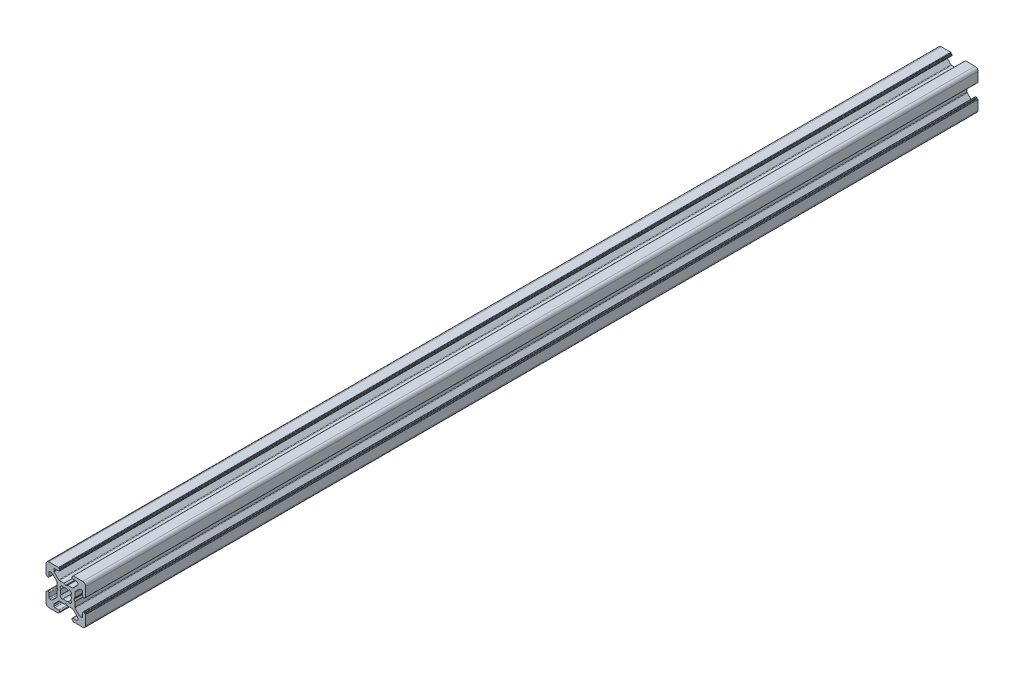
SolidWorks part; units mm, degrees
material "3.1355 (EN-AW 2024)"
ref_plane "Спереди" through (0, 0, 0) normal (0, 0, 1) x (1, 0, 0)
ref_plane "Сверху" through (0, 0, 0) normal (0, 1, 0) x (1, 0, 0)
ref_plane "Справа" through (0, 0, 0) normal (1, 0, 0) x (0, 0, -1)
sketch "Model" plane through (0, 0, 0) normal (0, 0, 1) x (1, 0, 0)
  line L0 (-1.9139, 2.9896) -> (-1.2582, 2.4453)
  line L1 (1.2582, 2.4453) -> (1.9139, 2.9896)
  line L2 (2.9922, 1.9099) -> (2.4453, 1.2582)
  line L3 (2.4453, -1.2582) -> (2.9922, -1.9099)
  line L4 (1.9139, -2.9896) -> (1.2582, -2.4453)
  line L5 (-1.2582, -2.4453) -> (-1.9139, -2.9896)
  line L6 (-2.9922, -1.9099) -> (-2.4453, -1.2582)
  line L7 (-2.4453, 1.2582) -> (-2.9922, 1.9099)
  line L8 (5.6579, 4.5972) -> (5.7096, 4.7904)
  line L9 (5.7096, 4.7904) -> (5.9028, 4.8421)
  line L10 (5.9028, 4.8421) -> (6.9142, 5.8536)
  line L11 (7.2678, 6) -> (8, 6)
  line L12 (8.5, 5.5) -> (8.5, 3.6)
  line L13 (9, 3.1) -> (9.3, 3.1)
  line L14 (9.5, 3.3) -> (9.5, 3.35)
  line L15 (9.7, 3.55) -> (9.8, 3.55)
  line L16 (10, 3.75) -> (10, 8.5)
  line L17 (8.5, 10) -> (3.75, 10)
  line L18 (3.55, 9.8) -> (3.55, 9.7)
  line L19 (3.35, 9.5) -> (3.3, 9.5)
  line L20 (3.1, 9.3) -> (3.1, 9)
  line L21 (3.6, 8.5) -> (5.5, 8.5)
  line L22 (6, 8) -> (6, 7.2678)
  line L23 (5.8536, 6.9142) -> (3.5858, 4.6464)
  line L24 (3.2322, 4.5) -> (0.9536, 4.5)
  line L25 (0.8536, 4.4732) -> (0.1, 4.0381)
  line L26 (-0.1, 4.0381) -> (-0.8536, 4.4732)
  line L27 (-0.9536, 4.5) -> (-3.2322, 4.5)
  line L28 (-3.5858, 4.6464) -> (-5.8536, 6.9142)
  line L29 (-6, 7.2678) -> (-6, 8)
  line L30 (-5.5, 8.5) -> (-3.6, 8.5)
  line L31 (-3.1, 9) -> (-3.1, 9.3)
  line L32 (-3.3, 9.5) -> (-3.35, 9.5)
  line L33 (-3.55, 9.7) -> (-3.55, 9.8)
  line L34 (-3.75, 10) -> (-8.5, 10)
  line L35 (-10, 8.5) -> (-10, 3.75)
  line L36 (-9.8, 3.55) -> (-9.7, 3.55)
  line L37 (-9.5, 3.35) -> (-9.5, 3.3)
  line L38 (-9.3, 3.1) -> (-9, 3.1)
  line L39 (-8.5, 3.6) -> (-8.5, 5.5)
  line L40 (-8, 6) -> (-7.2678, 6)
  line L41 (-6.9142, 5.8536) -> (-4.6464, 3.5858)
  line L42 (-4.5, 3.2322) -> (-4.5, 0.9536)
  line L43 (-4.4732, 0.8536) -> (-4.0381, 0.1)
  line L44 (-4.0381, -0.1) -> (-4.4732, -0.8536)
  line L45 (-4.5, -0.9536) -> (-4.5, -3.2322)
  line L46 (-4.6464, -3.5858) -> (-6.9142, -5.8536)
  line L47 (-7.2678, -6) -> (-8, -6)
  line L48 (-8.5, -5.5) -> (-8.5, -3.6)
  line L49 (-9, -3.1) -> (-9.3, -3.1)
  line L50 (-9.5, -3.3) -> (-9.5, -3.35)
  line L51 (-9.7, -3.55) -> (-9.8, -3.55)
  line L52 (-10, -3.75) -> (-10, -8.5)
  line L53 (-8.5, -10) -> (-3.75, -10)
  line L54 (-3.55, -9.8) -> (-3.55, -9.7)
  line L55 (-3.35, -9.5) -> (-3.3, -9.5)
  line L56 (-3.1, -9.3) -> (-3.1, -9)
  line L57 (-3.6, -8.5) -> (-5.5, -8.5)
  line L58 (-6, -8) -> (-6, -7.2678)
  line L59 (-5.8536, -6.9142) -> (-3.5858, -4.6464)
  line L60 (-3.2322, -4.5) -> (-0.9536, -4.5)
  line L61 (-0.8536, -4.4732) -> (-0.1, -4.0381)
  line L62 (0.1, -4.0381) -> (0.8536, -4.4732)
  line L63 (0.9536, -4.5) -> (3.2322, -4.5)
  line L64 (3.5858, -4.6464) -> (5.8536, -6.9142)
  line L65 (6, -7.2678) -> (6, -8)
  line L66 (5.5, -8.5) -> (3.6, -8.5)
  line L67 (3.1, -9) -> (3.1, -9.3)
  line L68 (3.3, -9.5) -> (3.35, -9.5)
  line L69 (3.55, -9.7) -> (3.55, -9.8)
  line L70 (3.75, -10) -> (8.5, -10)
  line L71 (10, -8.5) -> (10, -3.75)
  line L72 (9.8, -3.55) -> (9.7, -3.55)
  line L73 (9.5, -3.35) -> (9.5, -3.3)
  line L74 (9.3, -3.1) -> (9, -3.1)
  line L75 (8.5, -3.6) -> (8.5, -5.5)
  line L76 (8, -6) -> (7.2678, -6)
  line L77 (6.9142, -5.8536) -> (4.6464, -3.5858)
  line L78 (4.5, -3.2322) -> (4.5, -0.9536)
  line L79 (4.4732, -0.8536) -> (4.0381, -0.1)
  line L80 (4.0381, 0.1) -> (4.4732, 0.8536)
  line L81 (4.5, 0.9536) -> (4.5, 3.2322)
  line L82 (4.6464, 3.5858) -> (5.6579, 4.5972)
  arc A0 (-1.9139, 2.9896) -> (-2.9922, 1.9099) centre (0, 0) ccw
  arc A1 (1.2582, 2.4453) -> (-1.2582, 2.4453) centre (0, 0) ccw
  arc A2 (2.9922, 1.9099) -> (1.9139, 2.9896) centre (0, 0) ccw
  arc A3 (2.4453, -1.2582) -> (2.4453, 1.2582) centre (0, 0) ccw
  arc A4 (1.9139, -2.9896) -> (2.9922, -1.9099) centre (0, 0) ccw
  arc A5 (-1.2582, -2.4453) -> (1.2582, -2.4453) centre (0, 0) ccw
  arc A6 (-2.9922, -1.9099) -> (-1.9139, -2.9896) centre (0, 0) ccw
  arc A7 (-2.4453, 1.2582) -> (-2.4453, -1.2582) centre (0, 0) ccw
  arc A8 (7.2678, 6) -> (6.9142, 5.8536) centre (7.2678, 5.5) ccw
  arc A9 (8.5, 5.5) -> (8, 6) centre (8, 5.5) ccw
  arc A10 (8.5, 3.6) -> (9, 3.1) centre (9, 3.6) ccw
  arc A11 (9.3, 3.1) -> (9.5, 3.3) centre (9.3, 3.3) ccw
  arc A12 (9.7, 3.55) -> (9.5, 3.35) centre (9.7, 3.35) ccw
  arc A13 (9.8, 3.55) -> (10, 3.75) centre (9.8, 3.75) ccw
  arc A14 (10, 8.5) -> (8.5, 10) centre (8.5, 8.5) ccw
  arc A15 (3.75, 10) -> (3.55, 9.8) centre (3.75, 9.8) ccw
  arc A16 (3.35, 9.5) -> (3.55, 9.7) centre (3.35, 9.7) ccw
  arc A17 (3.3, 9.5) -> (3.1, 9.3) centre (3.3, 9.3) ccw
  arc A18 (3.1, 9) -> (3.6, 8.5) centre (3.6, 9) ccw
  arc A19 (6, 8) -> (5.5, 8.5) centre (5.5, 8) ccw
  arc A20 (5.8536, 6.9142) -> (6, 7.2678) centre (5.5, 7.2678) ccw
  arc A21 (3.2322, 4.5) -> (3.5858, 4.6464) centre (3.2322, 5) ccw
  arc A22 (0.9536, 4.5) -> (0.8536, 4.4732) centre (0.9536, 4.3) ccw
  arc A23 (-0.1, 4.0381) -> (0.1, 4.0381) centre (0, 4.2113) ccw
  arc A24 (-0.8536, 4.4732) -> (-0.9536, 4.5) centre (-0.9536, 4.3) ccw
  arc A25 (-3.5858, 4.6464) -> (-3.2322, 4.5) centre (-3.2322, 5) ccw
  arc A26 (-6, 7.2678) -> (-5.8536, 6.9142) centre (-5.5, 7.2678) ccw
  arc A27 (-5.5, 8.5) -> (-6, 8) centre (-5.5, 8) ccw
  arc A28 (-3.6, 8.5) -> (-3.1, 9) centre (-3.6, 9) ccw
  arc A29 (-3.1, 9.3) -> (-3.3, 9.5) centre (-3.3, 9.3) ccw
  arc A30 (-3.55, 9.7) -> (-3.35, 9.5) centre (-3.35, 9.7) ccw
  arc A31 (-3.55, 9.8) -> (-3.75, 10) centre (-3.75, 9.8) ccw
  arc A32 (-8.5, 10) -> (-10, 8.5) centre (-8.5, 8.5) ccw
  arc A33 (-10, 3.75) -> (-9.8, 3.55) centre (-9.8, 3.75) ccw
  arc A34 (-9.5, 3.35) -> (-9.7, 3.55) centre (-9.7, 3.35) ccw
  arc A35 (-9.5, 3.3) -> (-9.3, 3.1) centre (-9.3, 3.3) ccw
  arc A36 (-9, 3.1) -> (-8.5, 3.6) centre (-9, 3.6) ccw
  arc A37 (-8, 6) -> (-8.5, 5.5) centre (-8, 5.5) ccw
  arc A38 (-6.9142, 5.8536) -> (-7.2678, 6) centre (-7.2678, 5.5) ccw
  arc A39 (-4.5, 3.2322) -> (-4.6464, 3.5858) centre (-5, 3.2322) ccw
  arc A40 (-4.5, 0.9536) -> (-4.4732, 0.8536) centre (-4.3, 0.9536) ccw
  arc A41 (-4.0381, -0.1) -> (-4.0381, 0.1) centre (-4.2113, 0) ccw
  arc A42 (-4.4732, -0.8536) -> (-4.5, -0.9536) centre (-4.3, -0.9536) ccw
  arc A43 (-4.6464, -3.5858) -> (-4.5, -3.2322) centre (-5, -3.2322) ccw
  arc A44 (-7.2678, -6) -> (-6.9142, -5.8536) centre (-7.2678, -5.5) ccw
  arc A45 (-8.5, -5.5) -> (-8, -6) centre (-8, -5.5) ccw
  arc A46 (-8.5, -3.6) -> (-9, -3.1) centre (-9, -3.6) ccw
  arc A47 (-9.3, -3.1) -> (-9.5, -3.3) centre (-9.3, -3.3) ccw
  arc A48 (-9.7, -3.55) -> (-9.5, -3.35) centre (-9.7, -3.35) ccw
  arc A49 (-9.8, -3.55) -> (-10, -3.75) centre (-9.8, -3.75) ccw
  arc A50 (-10, -8.5) -> (-8.5, -10) centre (-8.5, -8.5) ccw
  arc A51 (-3.75, -10) -> (-3.55, -9.8) centre (-3.75, -9.8) ccw
  arc A52 (-3.35, -9.5) -> (-3.55, -9.7) centre (-3.35, -9.7) ccw
  arc A53 (-3.3, -9.5) -> (-3.1, -9.3) centre (-3.3, -9.3) ccw
  arc A54 (-3.1, -9) -> (-3.6, -8.5) centre (-3.6, -9) ccw
  arc A55 (-6, -8) -> (-5.5, -8.5) centre (-5.5, -8) ccw
  arc A56 (-5.8536, -6.9142) -> (-6, -7.2678) centre (-5.5, -7.2678) ccw
  arc A57 (-3.2322, -4.5) -> (-3.5858, -4.6464) centre (-3.2322, -5) ccw
  arc A58 (-0.9536, -4.5) -> (-0.8536, -4.4732) centre (-0.9536, -4.3) ccw
  arc A59 (0.1, -4.0381) -> (-0.1, -4.0381) centre (0, -4.2113) ccw
  arc A60 (0.8536, -4.4732) -> (0.9536, -4.5) centre (0.9536, -4.3) ccw
  arc A61 (3.5858, -4.6464) -> (3.2322, -4.5) centre (3.2322, -5) ccw
  arc A62 (6, -7.2678) -> (5.8536, -6.9142) centre (5.5, -7.2678) ccw
  arc A63 (5.5, -8.5) -> (6, -8) centre (5.5, -8) ccw
  arc A64 (3.6, -8.5) -> (3.1, -9) centre (3.6, -9) ccw
  arc A65 (3.1, -9.3) -> (3.3, -9.5) centre (3.3, -9.3) ccw
  arc A66 (3.55, -9.7) -> (3.35, -9.5) centre (3.35, -9.7) ccw
  arc A67 (3.55, -9.8) -> (3.75, -10) centre (3.75, -9.8) ccw
  arc A68 (8.5, -10) -> (10, -8.5) centre (8.5, -8.5) ccw
  arc A69 (10, -3.75) -> (9.8, -3.55) centre (9.8, -3.75) ccw
  arc A70 (9.5, -3.35) -> (9.7, -3.55) centre (9.7, -3.35) ccw
  arc A71 (9.5, -3.3) -> (9.3, -3.1) centre (9.3, -3.3) ccw
  arc A72 (9, -3.1) -> (8.5, -3.6) centre (9, -3.6) ccw
  arc A73 (8, -6) -> (8.5, -5.5) centre (8, -5.5) ccw
  arc A74 (6.9142, -5.8536) -> (7.2678, -6) centre (7.2678, -5.5) ccw
  arc A75 (4.5, -3.2322) -> (4.6464, -3.5858) centre (5, -3.2322) ccw
  arc A76 (4.5, -0.9536) -> (4.4732, -0.8536) centre (4.3, -0.9536) ccw
  arc A77 (4.0381, 0.1) -> (4.0381, -0.1) centre (4.2113, 0) ccw
  arc A78 (4.4732, 0.8536) -> (4.5, 0.9536) centre (4.3, 0.9536) ccw
  arc A79 (4.6464, 3.5858) -> (4.5, 3.2322) centre (5, 3.2322) ccw
  dimension "D1" = 20
extrude "База" add sketch "Model" against normal mid plane 449.5
